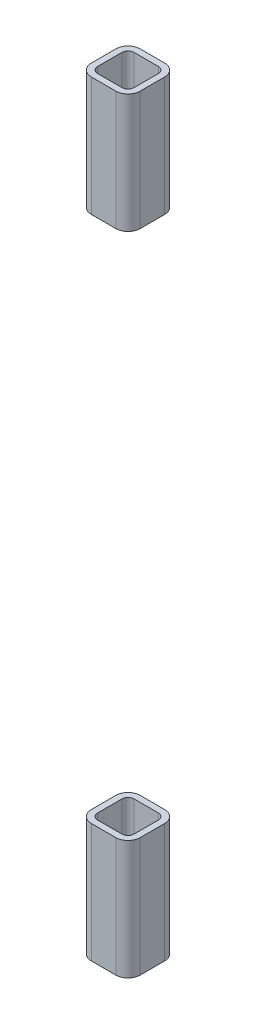
SolidWorks part; units mm, degrees
ref_plane "Alzado" through (0, 0, 0) normal (0, 0, 1) x (1, 0, 0)
ref_plane "Planta" through (0, 0, 0) normal (0, 1, 0) x (1, 0, 0)
ref_plane "Vista lateral" through (0, 0, 0) normal (1, 0, 0) x (0, 0, -1)
sketch "Croquis1" plane through (0, 0, 0) normal (0, 0, 1) x (1, 0, 0)
  line L0 (0, 0) -> (0, 798.4)
  dimension "D1" = 798.4
other "Tubo cuadrado 2 X 2 X 0.25(1)"
ref_plane "Plano1" through (0, 0, 0) normal (0, 1, 0) x (-1, 0, 0)
sketch "Sketch1" plane through (0, 0, 0) normal (0, 1, 0) x (-1, 0, 0)
  line L0 (-12.7, -19.05) -> (12.7, -19.05)
  line L1 (-19.05, -12.7) -> (-19.05, 12.7)
  line L2 (12.7, 19.05) -> (-12.7, 19.05)
  line L3 (19.05, 12.7) -> (19.05, -12.7)
  line L4 (-12.7, -25.4) -> (12.7, -25.4)
  line L5 (-25.4, -12.7) -> (-25.4, 12.7)
  line L6 (12.7, 25.4) -> (-12.7, 25.4)
  line L7 (25.4, 12.7) -> (25.4, -12.7)
  line L8 (0, 0) -> (19.05, 0) construction
  line L9 (0, 0) -> (0, 19.05) construction
  arc A0 (25.4, 12.7) -> (12.7, 25.4) centre (12.7, 12.7) ccw
  arc A1 (12.7, -25.4) -> (25.4, -12.7) centre (12.7, -12.7) ccw
  arc A2 (-25.4, -12.7) -> (-12.7, -25.4) centre (-12.7, -12.7) ccw
  arc A3 (-12.7, 25.4) -> (-25.4, 12.7) centre (-12.7, 12.7) ccw
  arc A4 (-12.7, 19.05) -> (-19.05, 12.7) centre (-12.7, 12.7) ccw
  arc A5 (19.05, 12.7) -> (12.7, 19.05) centre (12.7, 12.7) ccw
  arc A6 (12.7, -19.05) -> (19.05, -12.7) centre (12.7, -12.7) ccw
  arc A7 (-19.05, -12.7) -> (-12.7, -19.05) centre (-12.7, -12.7) ccw
  point P3 (0, 25.4)
  point P4 (25.4, 0)
  point P5 (0, -25.4)
  point P6 (-25.4, 0)
  point P7 (-25.4, 25.4)
  point P8 (-25.4, -25.4)
  point P33 (0, 0)
  point P35 (25.4, -25.4)
  point P36 (25.4, 25.4)
  point P37 (0, 0)
  dimension "D1" = 12.7
  dimension "Thickness" = 6.35
  dimension "V_leg" = 50.8
sketch "Croquis2" plane through (0, 0, 25.4) normal (0, 0, 1) x (1, 0, 0)
  line L0 (0, 0) -> (0, 798.4) construction
  line L1 (0, 798.4) -> (0, 399.2) construction
  line L2 (0, 399.2) -> (0, 124.2) construction
  line L3 (0, 399.2) -> (0, 674.2) construction
  line L4 (0, 124.2) -> (25.4, 124.2)
  line L5 (25.4, 798.4) -> (25.4, 0) construction
  line L6 (25.4, 124.2) -> (25.4, 674.2)
  line L7 (25.4, 674.2) -> (-25.4, 674.2)
  line L8 (-25.4, 798.4) -> (-25.4, 0) construction
  line L9 (-25.4, 674.2) -> (-25.4, 124.2)
  line L10 (-25.4, 124.2) -> (0, 124.2)
  line L11 (0, 124.2) -> (-1.4984, 123.577)
  line M2 (12.7, 0) -> (12.7, 798.4)
  line M4 (-12.7, 798.4) -> (-12.7, 0)
  dimension "D1" = 275
  dimension "D2" = 275
extrude "Cortar-Extruir1" cut sketch "Croquis2" against normal blind 101 contours L9 L10 L7 M4 | L10 L4 L7 M4 M2 | L6 L7 L4 M2
